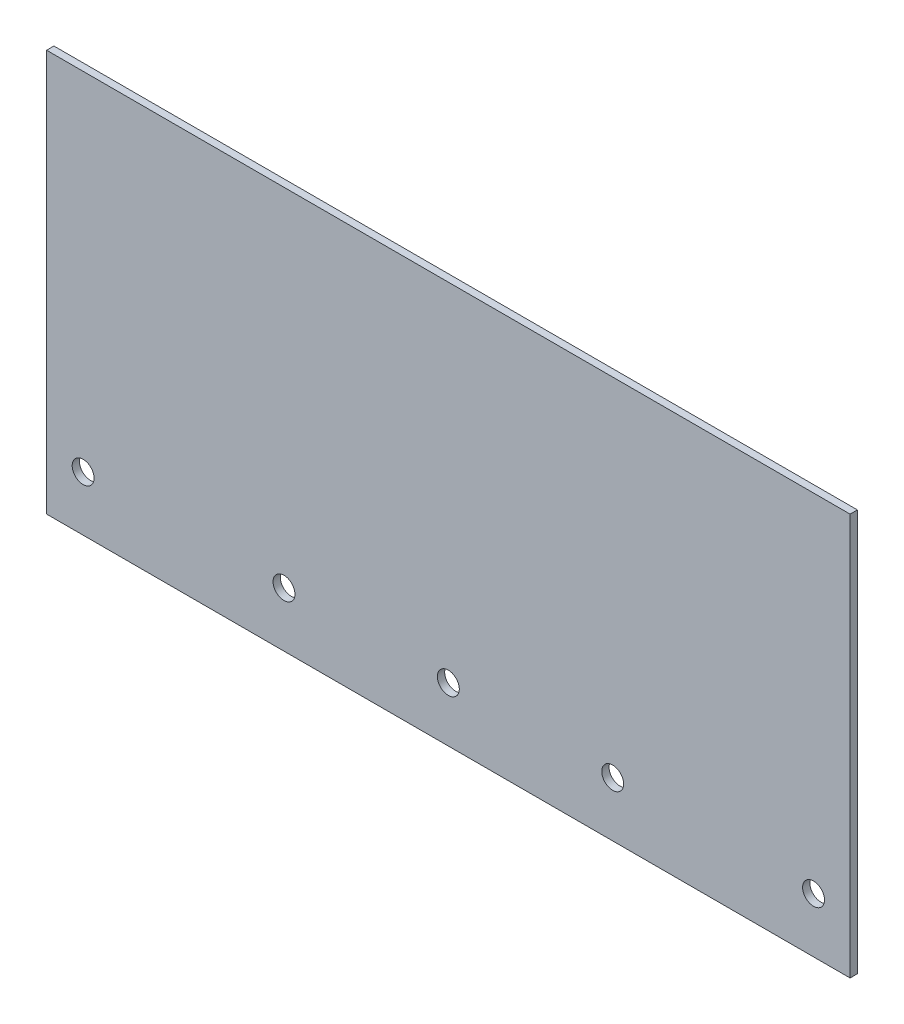
SolidWorks part; units mm, degrees
material "6061 Alloy"
ref_plane "Front Plane" through (0, 0, 0) normal (0, 0, 1) x (1, 0, 0)
ref_plane "Top Plane" through (0, 0, 0) normal (0, 1, 0) x (1, 0, 0)
ref_plane "Right Plane" through (0, 0, 0) normal (1, 0, 0) x (0, 0, -1)
sketch "Sketch1" plane through (0, 0, 0) normal (0, 0, 1) x (1, 0, 0)
  line L1 (-110, -55) -> (110, -55)
  line L2 (-110, -55) -> (-110, 55)
  line L3 (-110, 55) -> (110, 55)
  line L4 (110, -55) -> (110, 55)
  line L5 (-110, -55) -> (110, 55) construction
  line L6 (-110, 55) -> (110, -55) construction
  point P0 (0, 0)
  dimension "D1" = 220
  dimension "D2" = 110
extrude "Boss-Extrude1" add sketch "Sketch1" along normal blind 2
sketch "Sketch2" plane through (0, 0, 2) normal (0, 0, 1) x (1, 0, 0)
  line L0 (-110, 55) -> (-110, -55) construction
  line L1 (110, -55) -> (110, 55) construction
  line L2 (110, 55) -> (-110, 55) construction
  circle A0 centre (-100, -40) radius 3
  circle A1 centre (0, -40) radius 3
  circle A2 centre (-45, -40) radius 3
  circle A3 centre (45, -40) radius 3
  circle A4 centre (100, -40) radius 3
  dimension "D1" = 6
  dimension "D2" = 10
  dimension "D3" = 95
  dimension "D4" = 55
  dimension "D5" = 10
  dimension "D6" = 95
  dimension "D7" = 95
  dimension "D8" = 95
  dimension "D9" = 95
  dimension "D10" = 55
  dimension "D11" = 45
extrude "Cut-Extrude1" cut sketch "Sketch2" against normal through all
